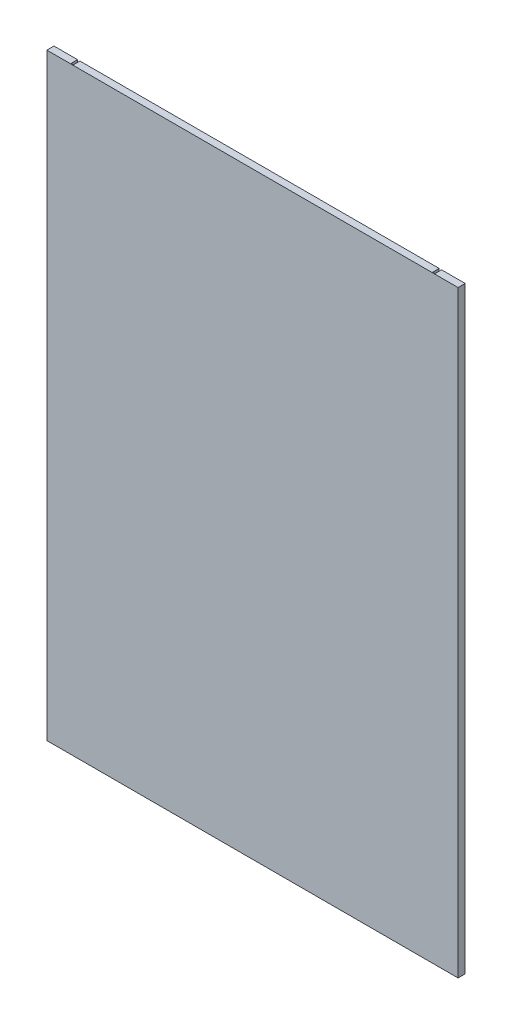
SolidWorks part; units mm, degrees
ref_plane "Front Plane" through (0, 0, 0) normal (0, 0, 1) x (1, 0, 0)
ref_plane "Top Plane" through (0, 0, 0) normal (0, 1, 0) x (1, 0, 0)
ref_plane "Right Plane" through (0, 0, 0) normal (1, 0, 0) x (0, 0, -1)
sketch "Sketch1" plane through (0, 0, 0) normal (0, 1, 0) x (1, 0, 0)
  line L0 (-87, 0) -> (-87, 3)
  line L1 (-87, 3) -> (-77, 3)
  line L2 (-77, 3) -> (-77, 0.2)
  line L4 (77, 0.2) -> (77, 3)
  line L5 (77, 3) -> (87, 3)
  line L6 (87, 3) -> (87, 0)
  line L7 (87, 0) -> (-87, 0)
  line L8 (-77, 0.2) -> (-76, 0.2)
  line L9 (-76, 0.2) -> (-76, 3)
  line L10 (-76, 3) -> (76, 3)
  line L11 (76, 3) -> (76, 0.2)
  line L12 (76, 0.2) -> (77, 0.2)
  point P10 (0, 0)
  point P14 (-0.2457, 0.1191)
  point P16 (-0.369, 0.2)
  point P17 (0, 0)
  point P18 (-78.508, 3)
  point P19 (2.4202, 3)
  point P20 (84.6143, 3)
  point P21 (-87, 0)
  point P22 (-87, 3)
  dimension "D1" = 0.2
  dimension "D2" = 3
  dimension "D3" = 152
  dimension "D4" = 1
  dimension "D5" = 10
extrude "Boss-Extrude1" add sketch "Sketch1" along normal blind 253
